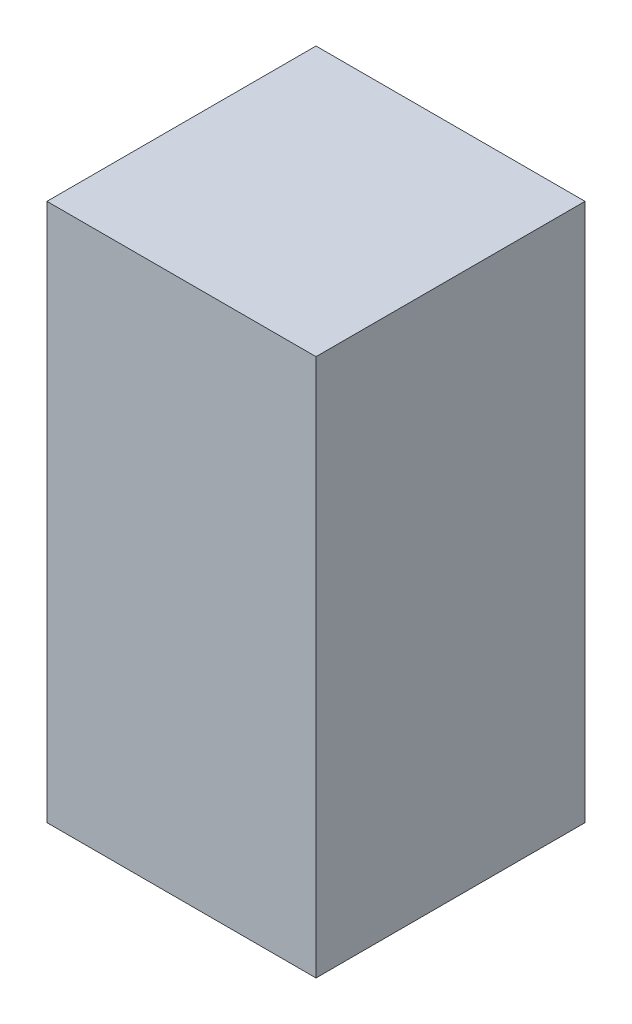
SolidWorks part; units mm, degrees
ref_plane "Front Plane" through (0, 0, 0) normal (0, 0, 1) x (1, 0, 0)
ref_plane "Top Plane" through (0, 0, 0) normal (0, 1, 0) x (1, 0, 0)
ref_plane "Right Plane" through (0, 0, 0) normal (1, 0, 0) x (0, 0, -1)
sketch "Sketch1" plane through (0, 0, 0) normal (0, 1, 0) x (1, 0, 0)
  line L1 (-75, 75) -> (75, 75)
  line L2 (-75, 75) -> (-75, -75)
  line L3 (-75, -75) -> (75, -75)
  line L4 (75, 75) -> (75, -75)
  point P9 (0.2996, 0.6055)
  dimension "D1" = 150
  dimension "D2" = 150
  dimension "D3" = 75
  dimension "D4" = 75
extrude "Boss-Extrude1" add sketch "Sketch1" along normal blind 300
equation "\"D3@Sketch1\"=\"D1@Sketch1\"/2"
equation "\"D4@Sketch1\"=\"D2@Sketch1\"/2"
